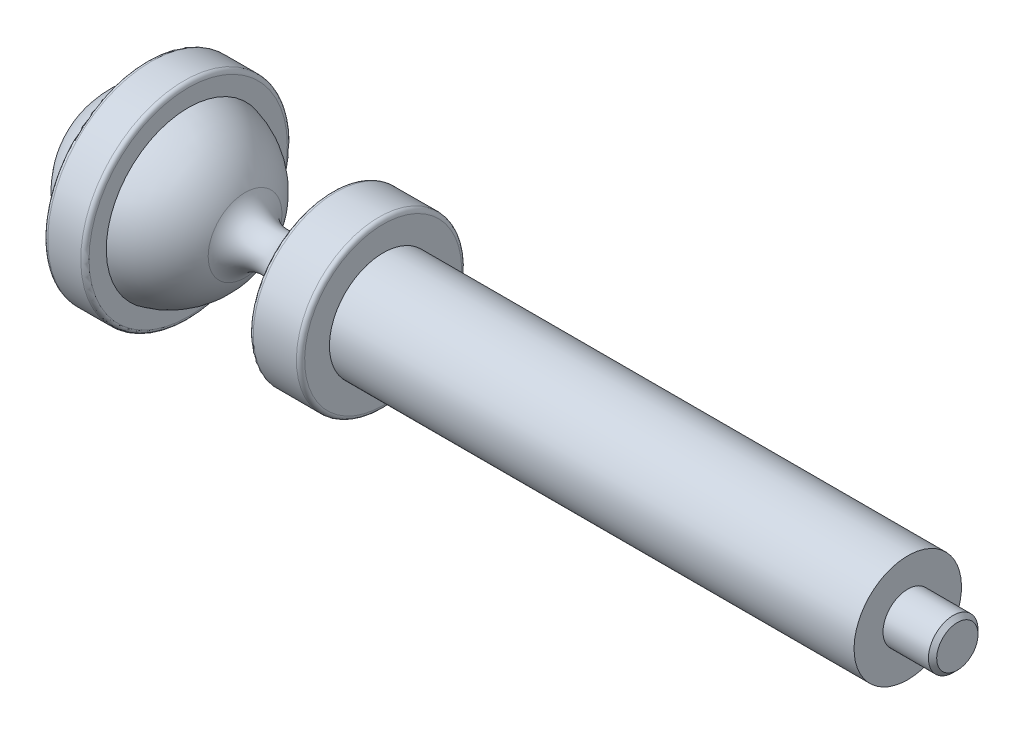
SolidWorks part; units mm, degrees
ref_plane "Płaszczyzna przednia" through (0, 0, 0) normal (0, 0, 1) x (1, 0, 0)
ref_plane "Płaszczyzna górna" through (0, 0, 0) normal (0, 1, 0) x (1, 0, 0)
ref_plane "Płaszczyzna prawa" through (0, 0, 0) normal (1, 0, 0) x (0, 0, -1)
sketch "Sketch1" plane through (0, 0, 0) normal (0, 0, 1) x (1, 0, 0)
  line L0 (0, 0) -> (105.5, 0)
  line L1 (105.5, 0) -> (105.5, 2.5)
  line L2 (105, 3) -> (99.5, 3)
  line L3 (99.5, 3) -> (99.5, 6.5)
  line L4 (99.5, 6.5) -> (36, 6.5)
  line L5 (36, 6.5) -> (36, 10)
  line L6 (36, 10) -> (30, 10)
  line L8 (7.4, 9.7779) -> (7.4, 12.5)
  line L9 (7.4, 12.5) -> (12.4, 12.5)
  line L10 (12.4, 12.5) -> (12.4, 9.91)
  line L11 (30, 10) -> (26.2613, 4.0845)
  line L12 (105.5, 2.5) -> (105, 3)
  arc A1 (19.2868, 4.464) -> (12.4, 9.91) centre (10.16, 0) ccw
  arc A2 (26.2613, 4.0845) -> (19.2868, 4.464) centre (22.88, 6.2215) cw
  arc A3 (7.4, 9.7779) -> (0, 0) centre (10.16, 0) ccw
  point P3 (105.5, 3)
  point P16 (18.4966, 7.7023)
  dimension "D6" = 30
  dimension "D8" = 10
  dimension "D7" = 4
  dimension "D10" = 10.16
  dimension "D1" = 63.5
  dimension "D2" = 3
  dimension "D3" = 6.5
  dimension "D4" = 6
  dimension "D5" = 6
  dimension "D9" = 12.5
  dimension "D11" = 5
  dimension "D12" = 7.4
  dimension "D13" = 22.88
revolve "Revolve1" add sketch "Sketch1" angle 360 about L0
cosmetic thread "Cosmetic Thread1"
fillet "Fillet1" radius 0.5 4 edges at (36, -10, 0) (30, -10, 0) (12.4, -12.5, 0) (7.4, -12.5, 0)
